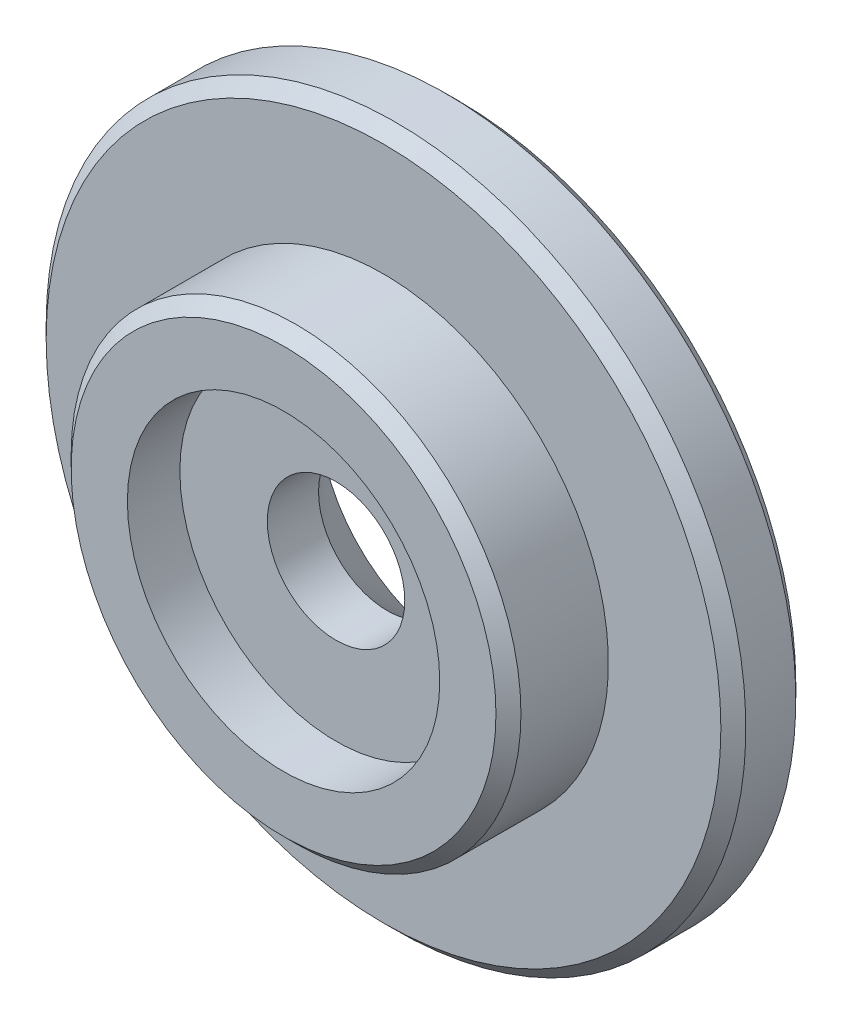
SolidWorks part; units mm, degrees
ref_plane "前视基准面" through (0, 0, 0) normal (0, 0, 1) x (1, 0, 0)
ref_plane "上视基准面" through (0, 0, 0) normal (0, 1, 0) x (1, 0, 0)
ref_plane "右视基准面" through (0, 0, 0) normal (1, 0, 0) x (0, 0, -1)
sketch "草图1" plane through (0, 0, 0) normal (0, 0, 1) x (1, 0, 0)
  circle A0 centre (0, 0) radius 9
  dimension "D1" = 18
extrude "凸台-拉伸1" add sketch "草图1" along normal blind 4
sketch "草图2" plane through (0, 0, 0) normal (0, 0, -1) x (-1, 0, 0)
  circle A0 centre (0, 0) radius 14
extrude "凸台-拉伸2" add sketch "草图2" along normal blind 3
sketch "草图3" plane through (0, 0, 4) normal (0, 0, 1) x (1, 0, 0)
  circle A0 centre (0, 0) radius 6.25
extrude "切除-拉伸1" cut sketch "草图3" against normal blind 2.1
hole_wizard "打孔尺寸根据开槽半沉头木螺钉的类型1" positions "草图5" profile "草图4" countersink size "M5" standard "GB" end condition through all
sketch "草图5" plane through (0, 0, -3) normal (0, 0, -1) x (-1, 0, 0)
  point P0 (0, 0)
sketch "草图4" plane through (0, 0, -3) normal (1, 0, 0) x (0, 1, 0)
  line L0 (0, 0) -> (0, 7)
  line L1 (0, 7) -> (2.75, 7)
  line L2 (2.75, 7) -> (2.75, 2.85)
  line L3 (2.75, 2.85) -> (5.6, 0)
  line L5 (5.6, 0) -> (0, 0)
  line L6 (-2.75, 2.85) -> (-5.6, 0) construction
  line L11 (0, -6.35) -> (0, 107.95) construction
  dimension "通孔孔直径" = 5.5
  dimension "通孔孔深度" = 7
  dimension "近端锥形沉头孔直径" = 11.2
  dimension "近端锥形沉头孔角度" = 90
chamfer "倒角1" distance 0.5 angle 45 3 edges at (-14, 0, -3) (-14, 0, 0) (9, 0, 4)
